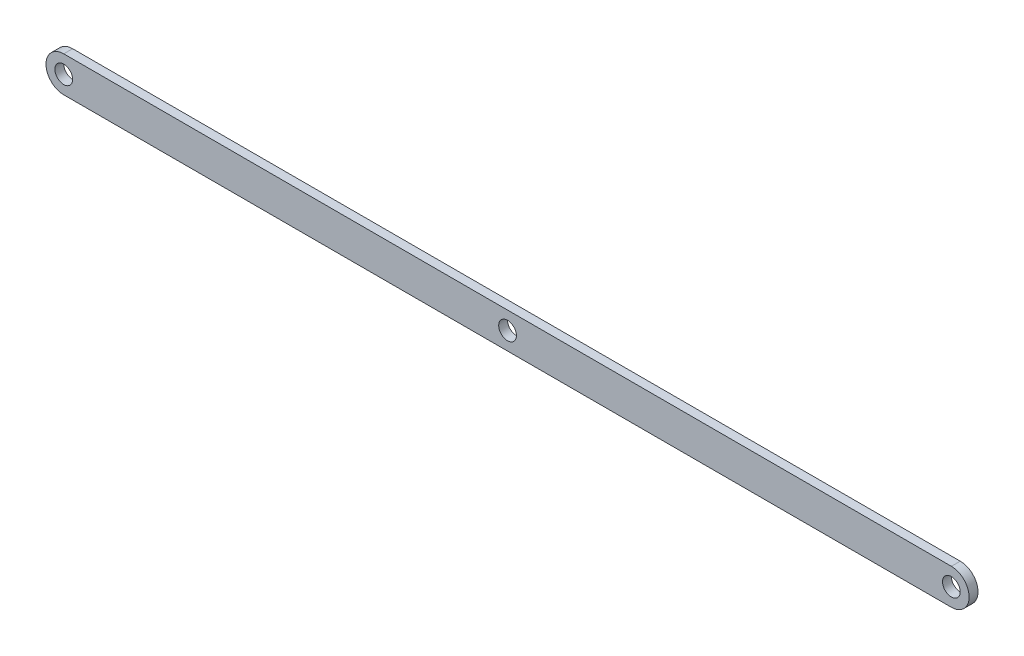
SolidWorks part; units mm, degrees
ref_plane "Front Plane" through (0, 0, 0) normal (0, 0, 1) x (1, 0, 0)
ref_plane "Top Plane" through (0, 0, 0) normal (0, 1, 0) x (1, 0, 0)
ref_plane "Right Plane" through (0, 0, 0) normal (1, 0, 0) x (0, 0, -1)
sketch "Sketch1" plane through (0, 0, 0) normal (0, 0, 1) x (1, 0, 0)
  line L0 (-250, 0) -> (250, 0) construction
  line L1 (-250, 10) -> (250, 10)
  line L2 (-250, -10) -> (250, -10)
  arc A0 (-250, 10) -> (-250, -10) centre (-250, 0) ccw
  arc A1 (250, -10) -> (250, 10) centre (250, 0) ccw
  circle A2 centre (-250, 0) radius 5
  circle A3 centre (0, 0) radius 5
  circle A4 centre (250, 0) radius 5
  point P2 (0, 0)
  dimension "D3" = 10
  dimension "D1" = 20
  dimension "D2" = 500
  dimension "D4" = 3
extrude "Boss-Extrude1" add sketch "Sketch1" along normal blind 5
